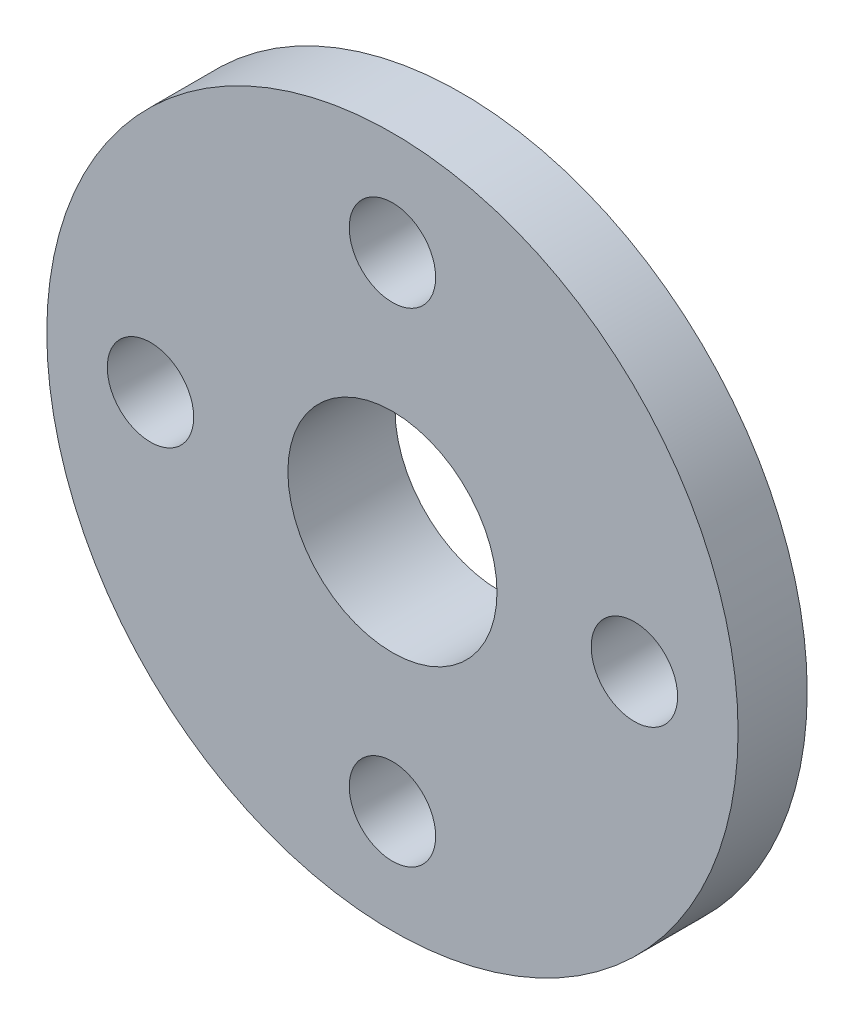
SolidWorks part; units mm, degrees
ref_plane "Front Plane" through (0, 0, 0) normal (0, 0, 1) x (1, 0, 0)
ref_plane "Top Plane" through (0, 0, 0) normal (0, 1, 0) x (1, 0, 0)
ref_plane "Right Plane" through (0, 0, 0) normal (1, 0, 0) x (0, 0, -1)
ref_plane "基准面1" through (0, -19.9, 0) normal (0, 1, 0) x (1, 0, 0)
sketch "草图1" plane through (0, -19.9, 0) normal (0, 1, 0) x (1, 0, 0)
  line L0 (-29.1026, -9.476) -> (-39.1026, -9.476)
  line L1 (-39.1026, -9.476) -> (-39.1026, -11.476)
  line L2 (-39.1026, -11.476) -> (-29.1026, -11.476)
  line L3 (-29.1026, -11.476) -> (-29.1026, -9.476)
  line L4 (-39.1026, -9.476) -> (-39.1026, -11.476) construction
revolve "旋转1" add sketch "草图1" angle 360 about L4
sketch "草图2" plane through (0, 0, 9.476) normal (0, 0, -1) x (-1, 0, 0)
  circle A0 centre (39.1026, -19.9) radius 4.5
extrude "凸台-拉伸1" add sketch "草图2" along normal blind 1.1
hole_wizard "孔1" positions "草图4" profile "草图3" legacy
sketch "草图4" plane through (0, 0, 11.476) normal (0, 0, 1) x (1, 0, 0)
  point P0 (-39.1026, -19.9)
sketch "草图3" plane through (-39.1026, -19.9, 11.476) normal (1, 0, 0) x (0, -1, 0)
  line L0 (0, 0) -> (0, 3.1)
  line L1 (0, 3.1) -> (3.025, 3.1)
  line L2 (3.025, 3.1) -> (3.025, 0)
  line L3 (3.025, 0) -> (0, 0)
  line L4 (0, 110) -> (0, -10) construction
  dimension "直径" = 6.05
  dimension "深度" = 3.1
hole_wizard "Ø2.5 (2.5) 直径孔1" positions "草图6" profile "草图5" hole size "Ø2.5" standard "ANSI Metric"
sketch "草图6" plane through (0, 0, 11.476) normal (0, 0, 1) x (1, 0, 0)
  point P0 (-46.1026, -19.9)
  point P1 (-39.1026, -26.9)
  point P2 (-32.1026, -19.9)
  point P3 (-39.1026, -12.9)
sketch "草图5" plane through (-46.1026, -19.9, 11.476) normal (1, 0, 0) x (0, -1, 0)
  line L0 (0, 0) -> (0, 3.1)
  line L1 (0, 3.1) -> (1.25, 3.1)
  line L2 (1.25, 3.1) -> (1.25, 0)
  line L5 (1.25, 0) -> (0, 0)
  line L11 (0, -6.35) -> (0, 107.95) construction
  dimension "通孔孔直径" = 2.5
  dimension "通孔孔深度" = 3.1
